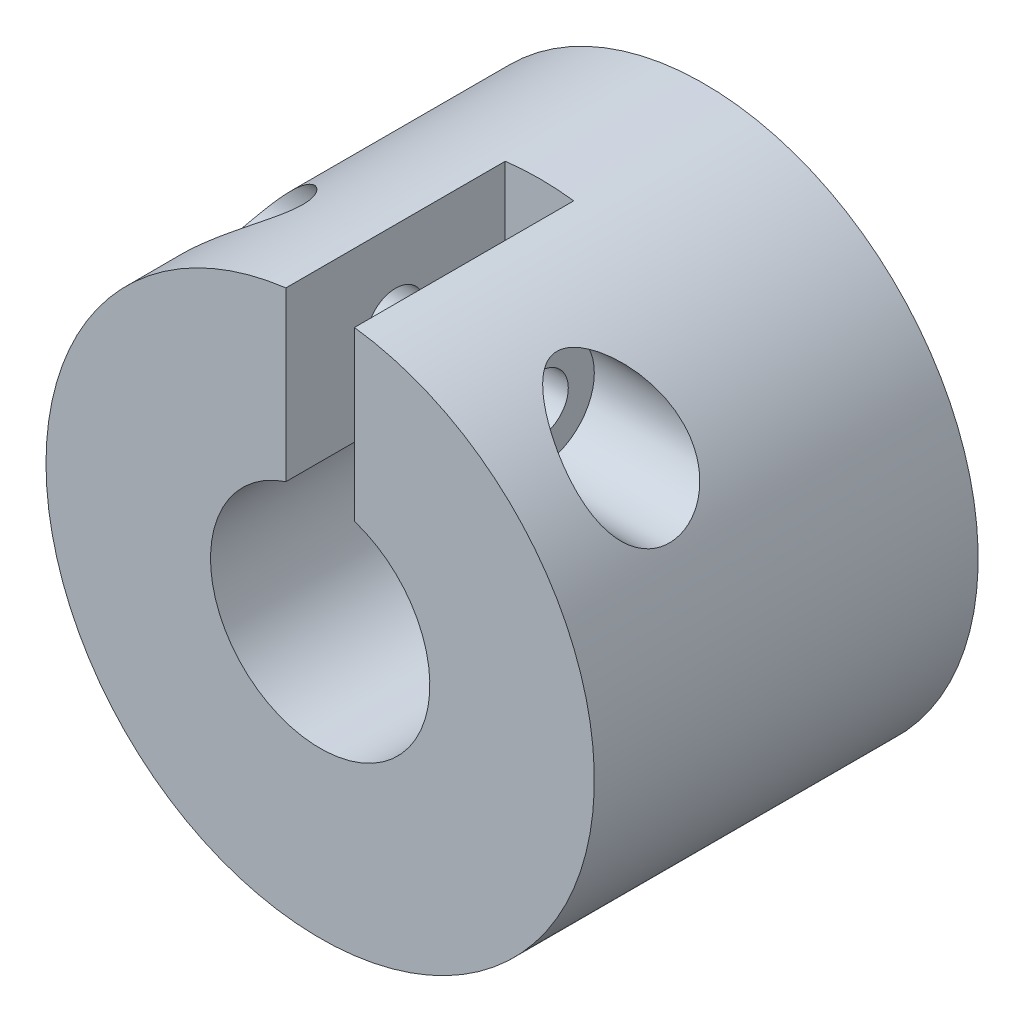
SolidWorks part; units mm, degrees
ref_plane "Front Plane" through (0, 0, 0) normal (0, 0, 1) x (1, 0, 0)
ref_plane "Top Plane" through (0, 0, 0) normal (0, 1, 0) x (1, 0, 0)
ref_plane "Right Plane" through (0, 0, 0) normal (1, 0, 0) x (0, 0, -1)
sketch "Sketch1" plane through (0, 0, 0) normal (0, 0, 1) x (1, 0, 0)
  circle A0 centre (0, 0) radius 4
  circle A1 centre (0, 0) radius 10
  dimension "D1" = 8
  dimension "D2" = 20
extrude "Boss-Extrude1" add sketch "Sketch1" along normal blind 8
sketch "Sketch2" plane through (0, 0, 8) normal (0, 0, 1) x (1, 0, 0)
  line L0 (-1.25, 0) -> (1.25, 0)
  line L2 (1.25, 0) -> (1.25, 11.0755)
  line L3 (1.25, 11.0755) -> (-1.25, 11.0755)
  line L4 (-1.25, 0) -> (-1.25, 11.0755)
  line L5 (0, 0) -> (-1.25, 11.0755) construction
  line L6 (1.25, 11.0755) -> (0, 0) construction
  point P0 (0, 0)
  dimension "D1" = 2.5
extrude "Cut-Extrude1" cut sketch "Sketch2" against normal through all
ref_plane "Plane1" through (-10, 0, 0) normal (-1, 0, 0) x (0, 0, 1)
sketch "Sketch3" plane through (-10, 0, 0) normal (-1, 0, 0) x (0, 0, 1)
  line L0 (0, 9.9216) -> (8, 3.7997) construction
  line L1 (8, 9.9216) -> (0, 3.7997) construction
  circle A0 centre (4, 6.8606) radius 1.05
  dimension "D1" = 2.1
extrude "Cut-Extrude2" cut sketch "Sketch3" against normal through all
sketch "Sketch4" plane through (-10, 0, 0) normal (-1, 0, 0) x (0, 0, 1)
  circle A0 centre (4, 6.8606) radius 2
  dimension "D1" = 4
extrude "Cut-Extrude3" cut sketch "Sketch4" against normal blind 6
sketch "Sketch5" plane through (0, 0, 0) normal (0, 0, -1) x (-1, 0, 0)
  line L0 (-1.25, 9.9216) -> (1.25, 3.7997) construction
  line L1 (1.25, 9.9216) -> (-1.25, 3.7997) construction
  line L2 (0, 6.8606) -> (0, 10.4953) construction
ref_plane "Plane2" through (0, 0, 0) normal (-1, 0, 0) x (0, 0, 1)
mirror "Mirror1" about plane through (0, 0, 0) normal (-1, 0, 0) of "Cut-Extrude3"
sketch "Sketch6" plane through (0, 0, 0) normal (0, 0, -1) x (-1, 0, 0)
  circle A0 centre (0, 0) radius 10
  arc A1 (-1.25, 9.9216) -> (1.25, 9.9216) centre (0, 0) ccw construction
extrude "Boss-Extrude3" add sketch "Sketch6" along normal blind 6
